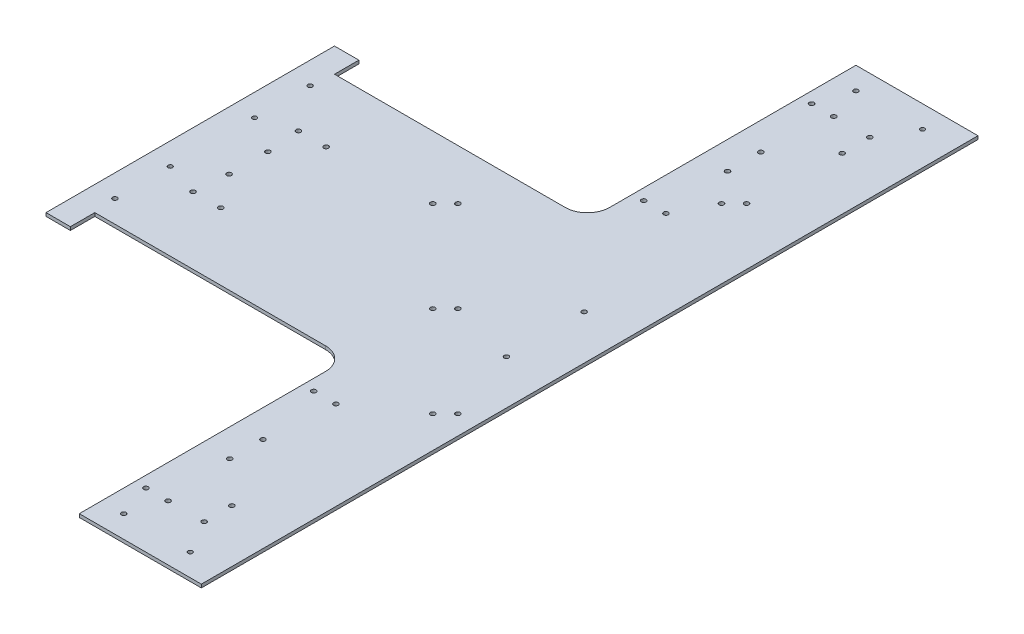
SolidWorks part; units mm, degrees
ref_plane "Front Plane" through (0, 0, 0) normal (0, 0, 1) x (1, 0, 0)
ref_plane "Top Plane" through (0, 0, 0) normal (0, 1, 0) x (1, 0, 0)
ref_plane "Right Plane" through (0, 0, 0) normal (1, 0, 0) x (0, 0, -1)
sketch "Sketch1" plane through (0, 0, 0) normal (0, 1, 0) x (1, 0, 0)
  line L0 (-110, 350) -> (-110, 108)
  line L1 (-110, 108) -> (-338, 108)
  line L2 (-338, 108) -> (-338, 130)
  line L3 (-338, 130) -> (-360, 130)
  line L4 (-360, 130) -> (-360, -130)
  line L5 (-360, 0) -> (1003.1457, 0) construction
  line L6 (0, 350) -> (0, -620.7989) construction
  line L7 (-338, -130) -> (-360, -130)
  line L8 (-338, -108) -> (-338, -130)
  line L9 (-110, -108) -> (-338, -108)
  line L10 (-110, 350) -> (110, 350)
  line L11 (-110, -350) -> (-110, -108)
  line L12 (-110, -350) -> (110, -350)
  line L13 (110, -350) -> (110, -108)
  line L14 (110, -108) -> (338, -108)
  line L15 (338, -108) -> (338, -130)
  line L16 (338, -130) -> (360, -130)
  line L17 (360, 130) -> (360, -130)
  line L18 (338, 130) -> (360, 130)
  line L19 (338, 108) -> (338, 130)
  line L20 (110, 108) -> (338, 108)
  line L21 (110, 350) -> (110, 108)
  point P17 (0, -350)
  dimension "D1" = 110
  dimension "D2" = 22
  dimension "D3" = 22
  dimension "D4" = 242
  dimension "D5" = 130
  dimension "D6" = 250
  dimension "D7" = 110
  dimension "D8" = 108
extrude "Boss-Extrude1" add sketch "Sketch1" along normal blind 3
sketch "Sketch2" plane through (0, 3, 0) normal (0, 1, 0) x (1, 0, 0)
  line L0 (360, -130) -> (360, 130) construction
  line L2 (338, 108) -> (110, 108) construction
  line L4 (0, 107.9437) -> (0, -458.275) construction
  line L5 (110, 108) -> (110, 350) construction
  line L6 (110, 350) -> (-110, 350) construction
  line L7 (-540.1841, 0) -> (-80.3508, 0) construction
  circle A0 centre (310, 47.5) radius 2.125
  circle A1 centre (285, 47.5) radius 2.125
  circle A2 centre (307.5, 17.5) radius 2.125
  circle A3 centre (307.5, -17.5) radius 2.125
  circle A4 centre (310, -47.5) radius 2.125
  circle A5 centre (285, -47.5) radius 2.125
  circle A6 centre (-285, -47.5) radius 2.125
  circle A7 centre (-310, -47.5) radius 2.125
  circle A8 centre (-307.5, -17.5) radius 2.125
  circle A9 centre (-307.5, 17.5) radius 2.125
  circle A10 centre (-285, 47.5) radius 2.125
  circle A11 centre (-310, 47.5) radius 2.125
  circle A13 centre (47.5, 300) radius 2.125
  circle A15 centre (47.5, 275) radius 2.125
  circle A16 centre (-47.5, 275) radius 2.125
  circle A17 centre (-47.5, 300) radius 2.125
  circle A18 centre (-47.5, -300) radius 2.125
  circle A19 centre (-47.5, -275) radius 2.125
  circle A20 centre (47.5, -275) radius 2.125
  circle A21 centre (47.5, -300) radius 2.125
  dimension "D1" = 4.25
  dimension "D2" = 4.25
  dimension "D3" = 4.25
  dimension "D4" = 4.25
  dimension "D5" = 4.25
  dimension "D6" = 4.25
  dimension "D15" = 4.25
  dimension "D16" = 4.25
  dimension "D7" = 50
  dimension "D8" = 25
  dimension "D9" = 95
  dimension "D10" = 35
  dimension "D11" = 60.5
  dimension "D12" = 90.5
  dimension "D13" = 52.5
  dimension "D14" = 110
  dimension "D17" = 50
  dimension "D18" = 25
  dimension "D19" = 62.5
  dimension "D20" = 108
extrude "Cut-Extrude1" cut sketch "Sketch2" against normal through all
sketch "Sketch3" plane through (0, 3, 0) normal (0, 1, 0) x (1, 0, 0)
  line L0 (360, -130) -> (360, 130) construction
  line L1 (338, 108) -> (110, 108) construction
  line L2 (-553.4456, 0) -> (-91.4299, 0) construction
  line L3 (0, 286.895) -> (0, -255.8046) construction
  line L4 (110, 108) -> (110, 350) construction
  line L5 (110, 350) -> (-110, 350) construction
  line L6 (-110, 350) -> (-110, 108) construction
  circle A0 centre (340, 38) radius 2
  circle A2 centre (340, -38) radius 2
  circle A3 centre (-340, -38) radius 2
  circle A4 centre (-340, 38) radius 2
  circle A5 centre (-30, 330) radius 2
  circle A7 centre (30, 330) radius 2
  circle A8 centre (30, -330) radius 2
  circle A9 centre (-30, -330) radius 2
  dimension "D1" = 4
  dimension "D6" = 4
  dimension "D7" = 80
  dimension "D2" = 20
  dimension "D3" = 70
  dimension "D4" = 108
  dimension "D5" = 110
  dimension "D8" = 20
extrude "Cut-Extrude2" cut sketch "Sketch3" against normal through all
sketch "Sketch5" plane through (0, 3, 0) normal (0, 1, 0) x (1, 0, 0)
  line L0 (110, 350) -> (-110, 350) construction
  line L1 (110, 108) -> (110, 350) construction
  line L2 (0, 224.365) -> (185.6725, 224.365) construction
  line L3 (90, 361.0488) -> (90, 126.2188) construction
  line L4 (0, 375.894) -> (0, 88.4107) construction
  line L5 (349.7475, 0) -> (-242.2654, 0) construction
  circle A0 centre (80, 300) radius 2.125
  circle A1 centre (80, 148.73) radius 2.125
  circle A2 centre (85.11, 239.365) radius 2.125
  circle A3 centre (85.11, 209.365) radius 2.125
  circle A4 centre (100, 148.73) radius 2.125
  circle A5 centre (100, 300) radius 2.125
  circle A6 centre (-100, 300) radius 2.125
  circle A7 centre (-100, 148.73) radius 2.125
  circle A8 centre (-85.11, 209.365) radius 2.125
  circle A9 centre (-85.11, 239.365) radius 2.125
  circle A10 centre (-80, 148.73) radius 2.125
  circle A11 centre (-80, 300) radius 2.125
  circle A12 centre (-80, -300) radius 2.125
  circle A13 centre (-80, -148.73) radius 2.125
  circle A14 centre (-85.11, -239.365) radius 2.125
  circle A15 centre (-85.11, -209.365) radius 2.125
  circle A16 centre (-100, -148.73) radius 2.125
  circle A17 centre (-100, -300) radius 2.125
  circle A18 centre (100, -300) radius 2.125
  circle A19 centre (100, -148.73) radius 2.125
  circle A20 centre (85.11, -209.365) radius 2.125
  circle A21 centre (85.11, -239.365) radius 2.125
  circle A22 centre (80, -148.73) radius 2.125
  circle A23 centre (80, -300) radius 2.125
  dimension "D1" = 4.25
  dimension "D2" = 4.25
  dimension "D6" = 4.25
  dimension "D7" = 4.25
  dimension "D3" = 151.27
  dimension "D4" = 50
  dimension "30" = 30
  dimension "D5" = 5.11
  dimension "D8" = 30
  dimension "D9" = 75.635
  dimension "D10" = 15
  dimension "D11" = 10
extrude "Cut-Extrude4" cut sketch "Sketch5" against normal blind 10
fillet "Fillet1" radius 20 4 edges at (110, 1.5, -108) (-110, 1.5, -108) (-110, 1.5, 108) (110, 1.5, 108)
sketch "Sketch6" plane through (0, 3, 0) normal (0, 1, 0) x (1, 0, 0)
  line L0 (-327.256, 327.256) -> (0, 0) construction
  line L1 (0, 429.479) -> (0, -412.5125) construction
  line L2 (-249.4214, 108) -> (110, -251.4214) construction
  line L3 (-226.7939, 108) -> (110, -228.7939) construction
  line L4 (327.256, 327.256) -> (0, 0) construction
  line L5 (-244.4559, 114.3482) -> (114.8318, -244.9395) construction
  line L6 (-130, 108) -> (-338, 108) construction
  line L7 (110, -350) -> (110, -128) construction
  circle A0 centre (53.3259, -194.7473) radius 2.125
  circle A1 centre (-192.7473, 51.3259) radius 2.125
  circle A2 centre (-28.6985, -112.7229) radius 2.125
  circle A3 centre (-110.7229, -30.6985) radius 2.125
  circle A4 centre (64.6396, -183.4335) radius 2.125
  circle A5 centre (-17.3848, -101.4092) radius 2.125
  circle A6 centre (-99.4092, -19.3848) radius 2.125
  circle A7 centre (-181.4335, 62.6396) radius 2.125
  circle A8 centre (-62.6396, 181.4335) radius 2.125
  circle A9 centre (19.3848, 99.4092) radius 2.125
  circle A10 centre (101.4092, 17.3848) radius 2.125
  circle A11 centre (183.4335, -64.6396) radius 2.125
  circle A12 centre (30.6985, 110.7229) radius 2.125
  circle A13 centre (112.7229, 28.6985) radius 2.125
  circle A14 centre (-51.3259, 192.7473) radius 2.125
  circle A15 centre (194.7473, -53.3259) radius 2.125
  point P23 (-69.7107, -71.7107)
  point P49 (71.7107, 69.7107)
  dimension "D3" = 4.25
  dimension "D5" = 4.25
  dimension "D8" = 4.25
  dimension "D10" = 4.25
  dimension "D1" = 45
  dimension "D2" = 100
  dimension "D4" = 16
  dimension "D6" = 348
  dimension "D7" = 174
  dimension "D9" = 116
  dimension "D11" = 116
  dimension "D12" = 8
extrude "Cut-Extrude5" cut sketch "Sketch6" against normal through all
sketch "Sketch7" plane through (0, 3, 0) normal (0, 1, 0) x (1, 0, 0)
  line L0 (0, 227.3539) -> (0, -244.3347) construction
  line L1 (-222.6371, 0) -> (245.907, 0) construction
  line L2 (360, -130) -> (360, 130) construction
  line L3 (338, 108) -> (130, 108) construction
  line L4 (110, 350) -> (-110, 350) construction
  line L5 (-110, 350) -> (-110, 128) construction
  circle A0 centre (340, 88) radius 2.1
  circle A1 centre (340, -88) radius 2.1
  circle A2 centre (-340, -88) radius 2.1
  circle A3 centre (-340, 88) radius 2.1
  circle A4 centre (-90, 330) radius 2.1
  circle A5 centre (90, 330) radius 2.1
  circle A6 centre (90, -330) radius 2.1
  circle A7 centre (-90, -330) radius 2.1
  dimension "D1" = 4.2
  dimension "D2" = 20
  dimension "D3" = 20
  dimension "D4" = 4.2
  dimension "D5" = 20
  dimension "D6" = 20
sketch "Sketch8" plane through (0, 3, 0) normal (0, 1, 0) x (1, 0, 0)
  line L0 (0, 227.3539) -> (0, -244.3347) construction
  line L1 (-222.6371, 0) -> (245.907, 0) construction
  line L2 (0, 89.3324) -> (0, -51.9249) construction
  line L3 (-114.1619, 0) -> (124.8762, 0) construction
  circle A0 centre (-40, 35) radius 2.1
  circle A1 centre (40, 35) radius 2.1
  circle A2 centre (40, -35) radius 2.1
  circle A3 centre (-40, -35) radius 2.1
  dimension "D1" = 4.2
  dimension "D2" = 40
  dimension "D3" = 35
extrude "Cut-Extrude6" cut sketch "Sketch8" against normal blind 10
extrude "Cut-Extrude7" cut sketch "Sketch7" against normal blind 10
sketch "Sketch9" plane through (0, 3, 0) normal (0, 1, 0) x (1, 0, 0)
  line L0 (110, 350) -> (-110, 350) construction
  line L1 (0, 350) -> (360, 350)
  line L2 (0, 350) -> (0, -350)
  line L3 (0, -350) -> (360, -350)
  line L4 (360, 350) -> (360, -350)
  line L5 (360, -130) -> (360, 130) construction
  line L6 (-110, -350) -> (110, -350) construction
  dimension "D1" = 0
  dimension "D2" = 0
extrude "Cut-Extrude8" cut sketch "Sketch9" against normal blind 10
equation "\"M3\"= 4.25mm"
equation "\"D1@Sketch2\"=\"M3\""
equation "\"D2@Sketch2\"=\"M3\""
equation "\"D3@Sketch2\"=\"M3\""
equation "\"D4@Sketch2\"=\"M3\""
equation "\"D5@Sketch2\"=\"M3\""
equation "\"D6@Sketch2\"=\"M3\""
equation "\"D15@Sketch2\"=\"M3\""
equation "\"D16@Sketch2\"=\"M3\""
equation "\"D6@Sketch5\"=\"M3\""
equation "\"D7@Sketch5\"=\"M3\""
equation "\"D2@Sketch5\"=\"M3\""
equation "\"D10@Sketch6\"=\"M3\""
equation "\"D3@Sketch6\"=\"M3\""
equation "\"D8@Sketch6\"=\"M3\""
equation "\"D5@Sketch6\"=\"M3\""
